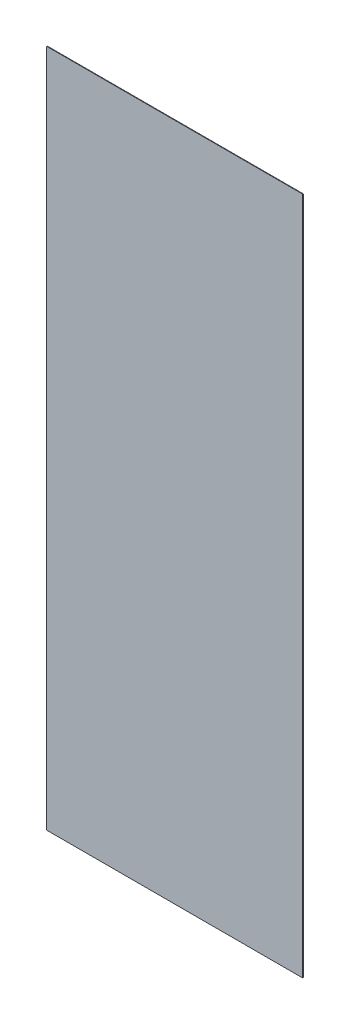
SolidWorks part; units mm, degrees
ref_plane "Front Plane" through (0, 0, 0) normal (0, 0, 1) x (1, 0, 0)
ref_plane "Top Plane" through (0, 0, 0) normal (0, 1, 0) x (1, 0, 0)
ref_plane "Right Plane" through (0, 0, 0) normal (1, 0, 0) x (0, 0, -1)
other "Configuration Table"
sketch "Sketch1" plane through (0, 0, 0) normal (0, 0, 1) x (1, 0, 0)
  line L1 (1.5, 120) -> (698.5, 120)
  line L2 (1.5, 120) -> (1.5, 1968.5)
  line L3 (1.5, 1968.5) -> (698.5, 1968.5)
  line L4 (698.5, 120) -> (698.5, 1968.5)
extrude "PRESS_dis_arka_1" add sketch "Sketch1" against normal blind 1.5 from offset 818.5 separate body
